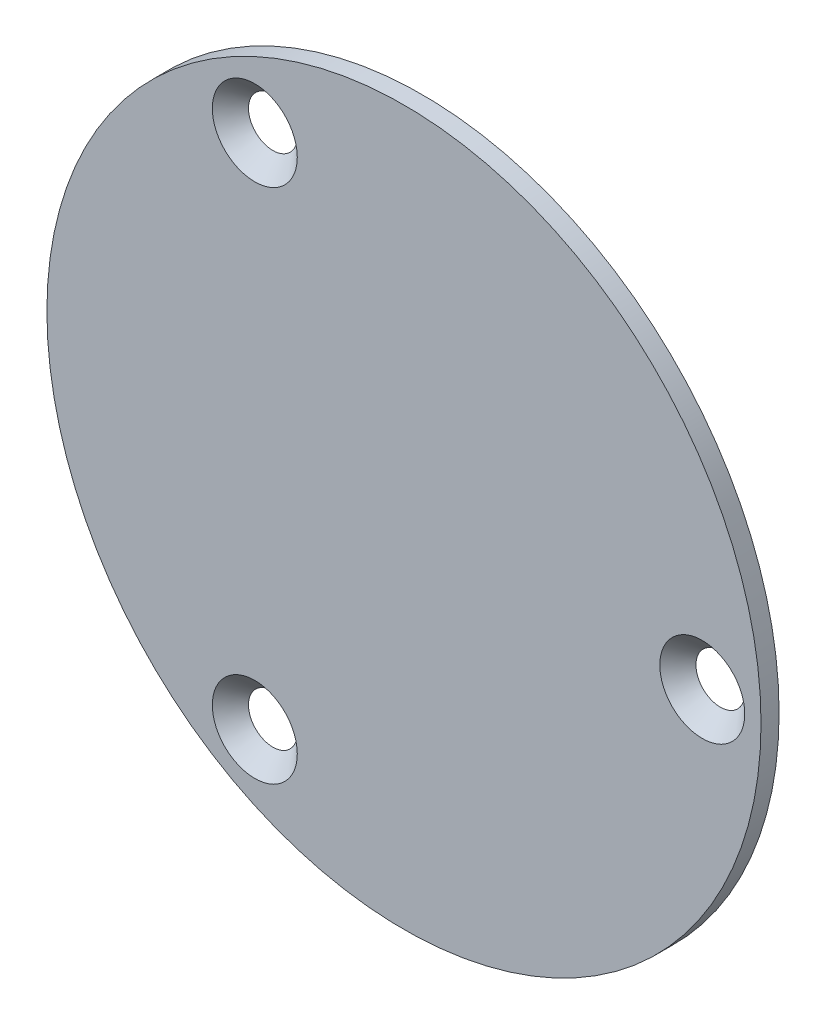
SolidWorks part; units mm, degrees
ref_plane "Front Plane" through (0, 0, 0) normal (0, 0, 1) x (1, 0, 0)
ref_plane "Top Plane" through (0, 0, 0) normal (0, 1, 0) x (1, 0, 0)
ref_plane "Right Plane" through (0, 0, 0) normal (1, 0, 0) x (0, 0, -1)
sketch "Sketch1" plane through (0, 0, 0) normal (0, 0, 1) x (1, 0, 0)
  circle A0 centre (0, 0) radius 39.5
  dimension "D1" = 79
extrude "Boss-Extrude1" add sketch "Sketch1" along normal blind 2
sketch "Sketch2" plane through (0, 0, 2) normal (0, 0, 1) x (1, 0, 0)
  circle A0 centre (0, 0) radius 33 construction
  point P0 (33, 0)
  point P7 (0, 0)
  dimension "D1" = 66
hole_wizard "CSK for M4 Flat Head Machine Screw1" positions "Sketch2" profile "Sketch3" countersink size "M4" standard "ANSI Metric"
sketch "Sketch3" plane through (33, 0, 2) normal (1, 0, 0) x (0, -1, 0)
  line L0 (0, 0) -> (0, 27.3919)
  line L1 (0, 27.3919) -> (2.25, 26.04)
  line L2 (2.25, 26.04) -> (2.25, 2.45)
  line L3 (2.25, 2.45) -> (4.7, 0)
  line L5 (4.7, 0) -> (0, 0)
  line L6 (-2.25, 2.45) -> (-4.7, 0) construction
  line L10 (0, 27.3919) -> (-2.25, 26.04) construction
  line L11 (0, -6.35) -> (0, 107.95) construction
  dimension "Hole Dia." = 4.5
  dimension "Hole Depth" = 26.04
  dimension "Near C'Sink Dia." = 9.4
  dimension "Near C'Sink Angle" = 90
  dimension "Drill Angle" = 118
pattern_circular "CirPattern1" count 3 over 360 about axis through (0, 0, 0) along (0, 0, 1) of "CSK for M4 Flat Head Machine Screw1"
